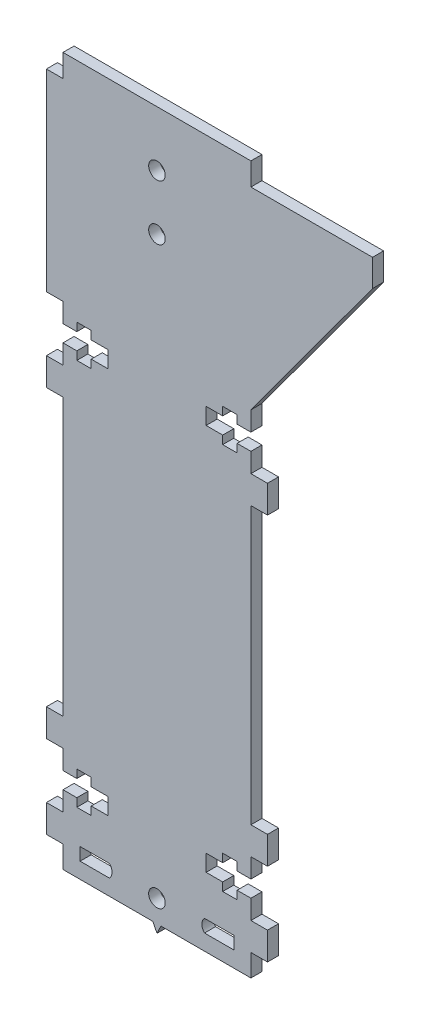
SolidWorks part; units mm, degrees
ref_plane "前视基准面" through (0, 0, 0) normal (0, 0, 1) x (1, 0, 0)
ref_plane "上视基准面" through (0, 0, 0) normal (0, 1, 0) x (1, 0, 0)
ref_plane "右视基准面" through (0, 0, 0) normal (1, 0, 0) x (0, 0, -1)
sketch "草图1" plane through (0, 0, 0) normal (0, 0, 1) x (1, 0, 0)
  line L25 (16.9939, -34) -> (16.9939, -84)
  line L26 (13.9, -105.15) -> (8.6, -105.15)
  line L27 (13.9, -102.85) -> (13.9, -105.15)
  line L34 (13.9, -102.85) -> (8.6, -102.85)
  line L35 (16.9939, 15.9) -> (16.9939, 20)
  line L36 (38.9939, 15.9) -> (16.9939, 15.9)
  line L37 (38.9939, 11) -> (38.9939, 15.9)
  line L40 (19.9939, -34) -> (16.9939, -34)
  line L41 (19.9939, -29) -> (16.9939, -29)
  line L42 (19.9939, -34) -> (19.9939, -29)
  line L47 (16.9939, -22.5) -> (16.9939, -19)
  line L64 (0, -108) -> (0, -109.5)
  line L77 (-13.9, -102.85) -> (-8.6, -102.85)
  line L78 (-13.9, -102.85) -> (-13.9, -105.15)
  line L79 (-13.9, -105.15) -> (-8.6, -105.15)
  line L94 (0, -109.5) -> (0.7212, -108)
  line L95 (0.7212, -108) -> (16.9939, -108)
  line L96 (-0.7212, -108) -> (-16.9939, -108)
  line L97 (0, -109.5) -> (-0.7212, -108)
  line L118 (16.9939, -19) -> (38.9939, 11)
  line L124 (16.9939, -25.5) -> (16.9939, -29)
  line L126 (14.4939, -25.5) -> (16.9939, -25.5)
  line L127 (14.4939, -21) -> (11.8939, -21)
  line L128 (11.8939, -21) -> (11.8939, -22.5)
  line L129 (11.8939, -22.5) -> (8.8939, -22.5)
  line L130 (11.8939, -25.5) -> (8.8939, -25.5)
  line L131 (11.8939, -27) -> (11.8939, -25.5)
  line L132 (14.4939, -27) -> (11.8939, -27)
  line L133 (16.9939, -22.5) -> (14.4939, -22.5)
  line L134 (14.4939, -22.5) -> (14.4939, -21)
  line L135 (8.8939, -22.5) -> (8.8939, -25.5)
  line L136 (14.4939, -25.5) -> (14.4939, -27)
  line L138 (-19.9939, -104) -> (-19.9939, -99)
  line L139 (-19.9939, -99) -> (-16.9939, -99)
  line L140 (-19.9939, -104) -> (-16.9939, -104)
  line L141 (-14.4939, -95.5) -> (-14.4939, -97)
  line L142 (-8.8939, -92.5) -> (-8.8939, -95.5)
  line L143 (-14.4939, -92.5) -> (-14.4939, -91)
  line L144 (-16.9939, -92.5) -> (-14.4939, -92.5)
  line L145 (-14.4939, -97) -> (-11.8939, -97)
  line L146 (-11.8939, -97) -> (-11.8939, -95.5)
  line L147 (-11.8939, -95.5) -> (-8.8939, -95.5)
  line L148 (-11.8939, -92.5) -> (-8.8939, -92.5)
  line L149 (-11.8939, -91) -> (-11.8939, -92.5)
  line L150 (-14.4939, -91) -> (-11.8939, -91)
  line L151 (-14.4939, -95.5) -> (-16.9939, -95.5)
  line L152 (-16.9939, -89) -> (-16.9939, -92.5)
  line L153 (-16.9939, -95.5) -> (-16.9939, -99)
  line L154 (-16.9939, -89) -> (-19.9939, -89)
  line L155 (-19.9939, -89) -> (-19.9939, -84)
  line L156 (-19.9939, -84) -> (-16.9939, -84)
  line L158 (-16.9939, -104) -> (-16.9939, -108)
  line L159 (19.9939, -84) -> (19.9939, -89)
  line L160 (19.9939, -89) -> (16.9939, -89)
  line L161 (19.9939, -84) -> (16.9939, -84)
  line L162 (14.4939, -92.5) -> (14.4939, -91)
  line L163 (8.8939, -95.5) -> (8.8939, -92.5)
  line L164 (14.4939, -95.5) -> (14.4939, -97)
  line L165 (16.9939, -95.5) -> (14.4939, -95.5)
  line L166 (14.4939, -91) -> (11.8939, -91)
  line L167 (11.8939, -91) -> (11.8939, -92.5)
  line L168 (11.8939, -92.5) -> (8.8939, -92.5)
  line L169 (11.8939, -95.5) -> (8.8939, -95.5)
  line L170 (11.8939, -97) -> (11.8939, -95.5)
  line L171 (14.4939, -97) -> (11.8939, -97)
  line L172 (14.4939, -92.5) -> (16.9939, -92.5)
  line L173 (16.9939, -99) -> (16.9939, -95.5)
  line L174 (16.9939, -92.5) -> (16.9939, -89)
  line L175 (16.9939, -99) -> (19.9939, -99)
  line L176 (19.9939, -99) -> (19.9939, -104)
  line L177 (19.9939, -104) -> (16.9939, -104)
  line L178 (16.9939, -104) -> (16.9939, -108)
  line L179 (-14.4939, -25.5) -> (-14.4939, -27)
  line L180 (-8.8939, -22.5) -> (-8.8939, -25.5)
  line L181 (-14.4939, -22.5) -> (-14.4939, -21)
  line L182 (-16.9939, -22.5) -> (-14.4939, -22.5)
  line L183 (-14.4939, -27) -> (-11.8939, -27)
  line L184 (-11.8939, -27) -> (-11.8939, -25.5)
  line L185 (-11.8939, -25.5) -> (-8.8939, -25.5)
  line L186 (-11.8939, -22.5) -> (-8.8939, -22.5)
  line L187 (-11.8939, -21) -> (-11.8939, -22.5)
  line L188 (-14.4939, -21) -> (-11.8939, -21)
  line L189 (-14.4939, -25.5) -> (-16.9939, -25.5)
  line L190 (-16.9939, -25.5) -> (-16.9939, -29)
  line L191 (-16.9939, -22.5) -> (-16.9939, -19)
  line L192 (-19.9939, -34) -> (-19.9939, -29)
  line L193 (-19.9939, -29) -> (-16.9939, -29)
  line L194 (-19.9939, -34) -> (-16.9939, -34)
  line L195 (-16.9939, -34) -> (-16.9939, -84)
  line L199 (-19.9939, -19) -> (-16.9939, -19)
  line L200 (-16.9939, 15.9) -> (-16.9939, 20)
  line L201 (-16.9939, 20) -> (16.9939, 20)
  line L202 (-16.9939, 15.9) -> (-19.9939, 15.9)
  line L203 (-19.9939, 15.9) -> (-19.9939, -19)
  circle A4 centre (0, -104) radius 1.5
  circle A6 centre (0, 0) radius 1.5
  circle A7 centre (0, 10) radius 1.5
  arc A8 (-8.6, -102.85) -> (-8.6, -105.15) centre (-9.75, -104) cw
  arc A9 (8.6, -102.85) -> (8.6, -105.15) centre (9.75, -104) ccw
extrude "凸台-拉伸1" add sketch "草图1" along normal blind 2
sketch "草图4" plane through (16.9939, 0, 0) normal (1, 0, 0) x (0, 0, -1)
  line L0 (-2, -108) -> (-2, -109.5)
  line L1 (-2, -109.5) -> (-1, -109.5)
  line L2 (-2, -109.5) -> (0, -109.5) construction
  line L3 (-1, -109.5) -> (-2, -108)
  line L4 (-1, -109.5) -> (0, -108)
  line L5 (0, -108) -> (0, -109.5)
  line L6 (0, -109.5) -> (0, -108) construction
  line L7 (0, -109.5) -> (-1, -109.5)
extrude "切除-拉伸1" [suppressed] cut sketch "草图4" against normal blind 20 contours L1 L3 L0 | L7 L5 L4
sketch "草图5" plane through (16.9939, 0, 0) normal (1, 0, 0) x (0, 0, -1)
  line L0 (-1, -92.5) -> (-1, -95.5)
  line L1 (-2, -92.5) -> (0, -92.5) construction
  line L2 (-2, -95.5) -> (0, -95.5) construction
  circle A0 centre (-1, -94) radius 1.5
sketch "草图6" plane through (-16.9939, 0, 0) normal (-1, 0, 0) x (0, 0, 1)
  line L0 (1, -92.5) -> (1, -95.5)
  line L1 (2, -92.5) -> (0, -92.5) construction
  line L2 (2, -95.5) -> (0, -95.5) construction
  circle A0 centre (1, -94) radius 1.5
